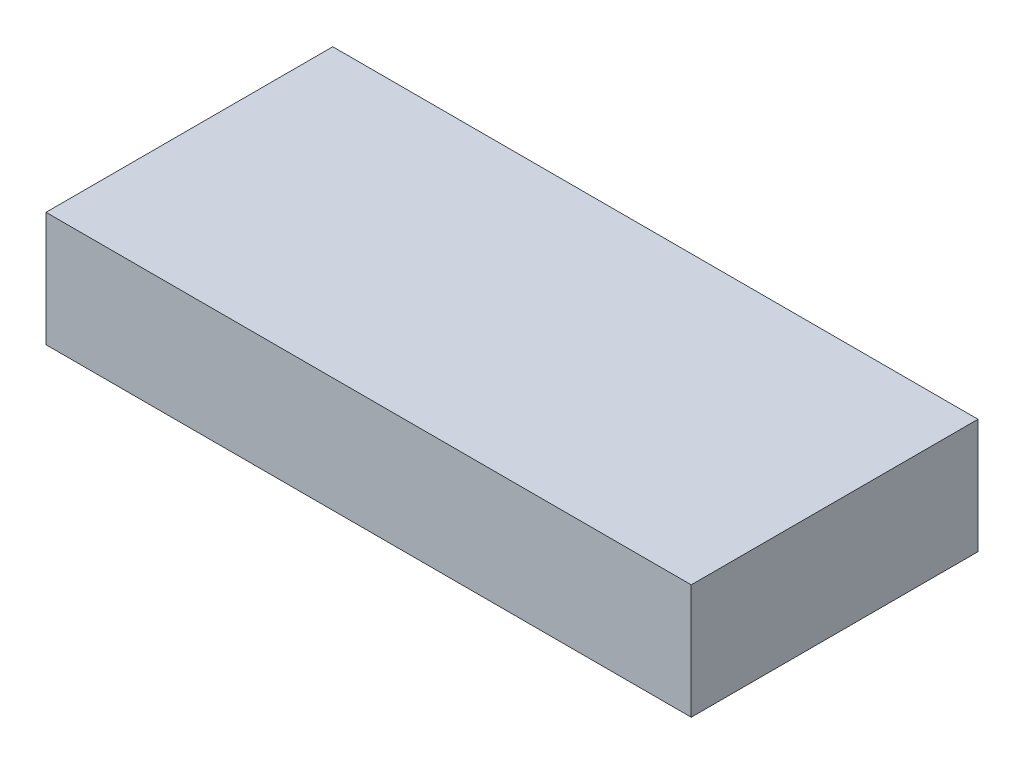
SolidWorks part; units mm, degrees
material "橡胶"
ref_plane "前视基准面" through (0, 0, 0) normal (0, 0, 1) x (1, 0, 0)
ref_plane "上视基准面" through (0, 0, 0) normal (0, 1, 0) x (1, 0, 0)
ref_plane "右视基准面" through (0, 0, 0) normal (1, 0, 0) x (0, 0, -1)
sketch "草图1" plane through (0, 0, 0) normal (0, 0, 1) x (1, 0, 0)
  line L1 (-22.5, -4) -> (22.5, -4)
  line L2 (-22.5, -4) -> (-22.5, 4)
  line L3 (-22.5, 4) -> (22.5, 4)
  line L4 (22.5, -4) -> (22.5, 4)
  line L5 (-22.5, -4) -> (22.5, 4) construction
  line L6 (-22.5, 4) -> (22.5, -4) construction
  point P0 (0, 0)
  dimension "D1" = 8
  dimension "D2" = 45
extrude "凸台-拉伸1" add sketch "草图1" along normal blind 20
